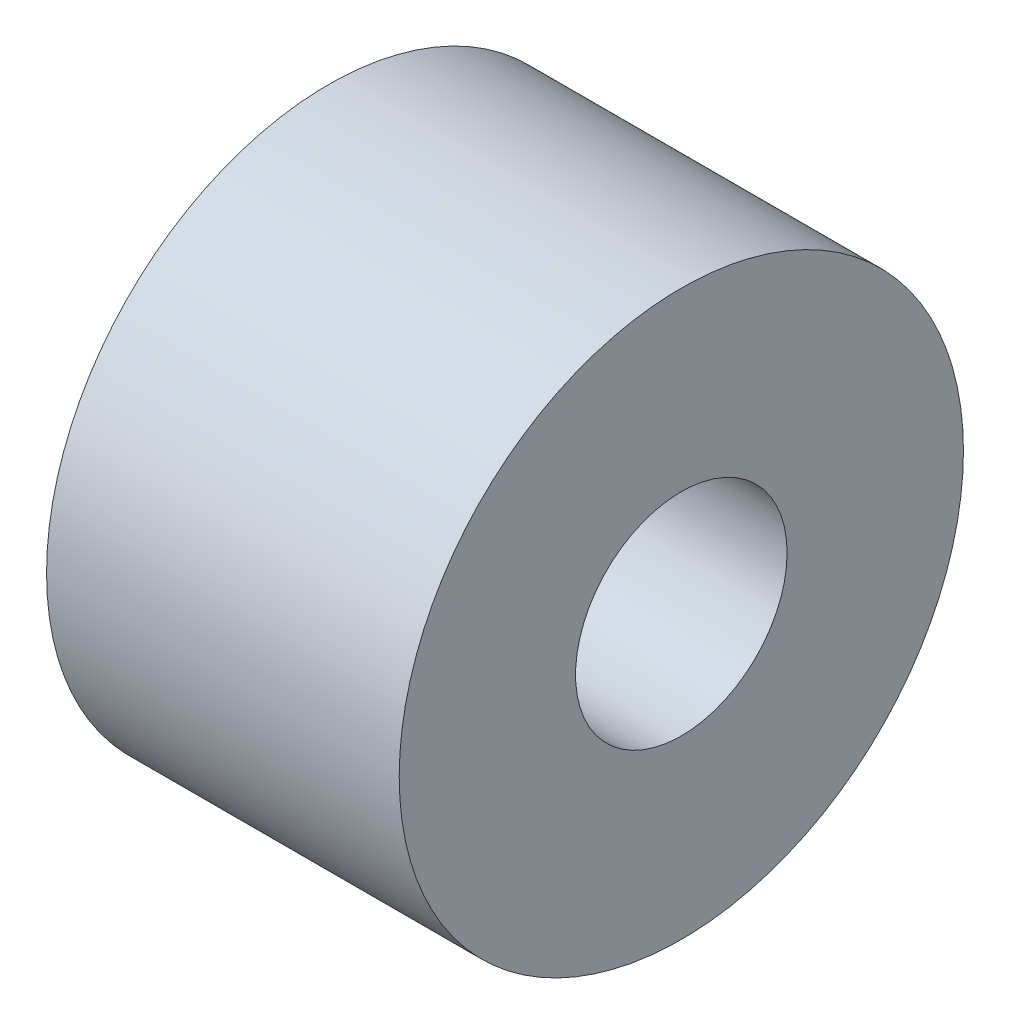
SolidWorks part; units mm, degrees
material "PE High Density"
ref_plane "Front Plane" through (0, 0, 0) normal (0, 0, 1) x (1, 0, 0)
ref_plane "Top Plane" through (0, 0, 0) normal (0, 1, 0) x (1, 0, 0)
ref_plane "Right Plane" through (0, 0, 0) normal (1, 0, 0) x (0, 0, -1)
sketch "Sketch1" plane through (0, 0, 0) normal (1, 0, 0) x (0, 0, -1)
  circle A0 centre (0, 0) radius 20
  circle A1 centre (0, 0) radius 7.5
  dimension "D1" = 15
  dimension "D2" = 40
extrude "Boss-Extrude1" add sketch "Sketch1" along normal blind 25
